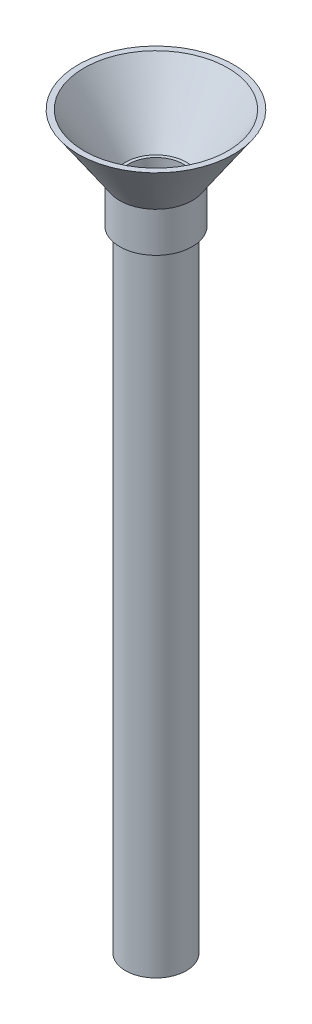
SolidWorks part; units mm, degrees
ref_plane "Front" through (0, 0, 0) normal (0, 0, 1) x (1, 0, 0)
ref_plane "Top" through (0, 0, 0) normal (0, 1, 0) x (1, 0, 0)
ref_plane "Right" through (0, 0, 0) normal (1, 0, 0) x (0, 0, -1)
sketch "Sketch1" plane through (0, 0, 0) normal (0, 1, 0) x (1, 0, 0)
  circle A0 centre (0, 0) radius 38.1
  circle A1 centre (0, 0) radius 34.1217
  dimension "D1" = 76.2
extrude "Boss-Extrude1" add sketch "Sketch1" along normal blind 838.2
sketch "Sketch2" plane through (0, 0, 0) normal (1, 0, 0) x (0, 0, -1)
  line L0 (-38.1, 788.2715) -> (-45.3136, 788.2715)
  line L1 (-38.1, 838.2) -> (-38.1, 0) construction
  line L2 (-45.3136, 788.2715) -> (-45.3136, 838.2)
  line L3 (-45.3136, 838.2) -> (-97.2342, 914.4)
  line L4 (-97.2342, 914.4) -> (-90.0206, 914.4)
  line L5 (-90.0206, 914.4) -> (-38.1, 838.2)
  line L6 (-38.1, 838.2) -> (-38.1, 788.2715)
  line L7 (-45.3136, 838.2) -> (-38.1, 838.2) construction
  dimension "D1" = 76.2
ref_axis "Axis1" through (0, 838.2, 0) along (0, -1, 0)
revolve "Revolve1" add sketch "Sketch2" angle 360 about axis through (0, 838.2, 0) along (0, -1, 0)
